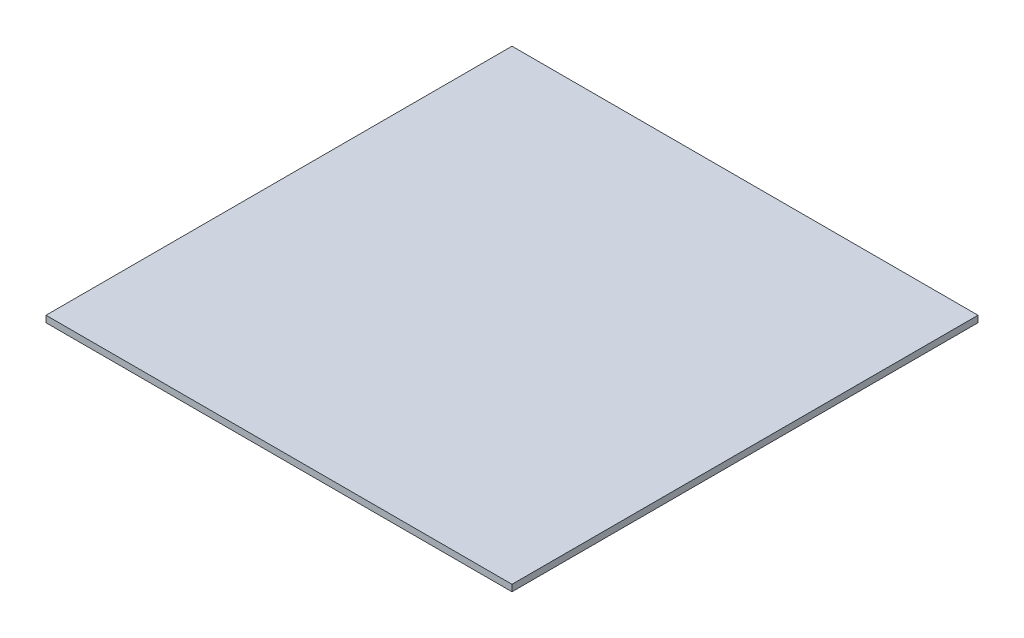
SolidWorks part; units mm, degrees
ref_plane "Front Plane" through (0, 0, 0) normal (0, 0, 1) x (1, 0, 0)
ref_plane "Top Plane" through (0, 0, 0) normal (0, 1, 0) x (1, 0, 0)
ref_plane "Right Plane" through (0, 0, 0) normal (1, 0, 0) x (0, 0, -1)
sketch "Sketch1" plane through (0, 0, 0) normal (0, 1, 0) x (1, 0, 0)
  line L1 (-107, -107) -> (107, -107)
  line L2 (-107, -107) -> (-107, 107)
  line L3 (-107, 107) -> (107, 107)
  line L4 (107, -107) -> (107, 107)
  line L5 (-107, -107) -> (107, 107) construction
  line L6 (-107, 107) -> (107, -107) construction
  point P0 (0, 0)
  dimension "D1" = 214
  dimension "D2" = 214
extrude "Boss-Extrude1" add sketch "Sketch1" along normal blind 3
